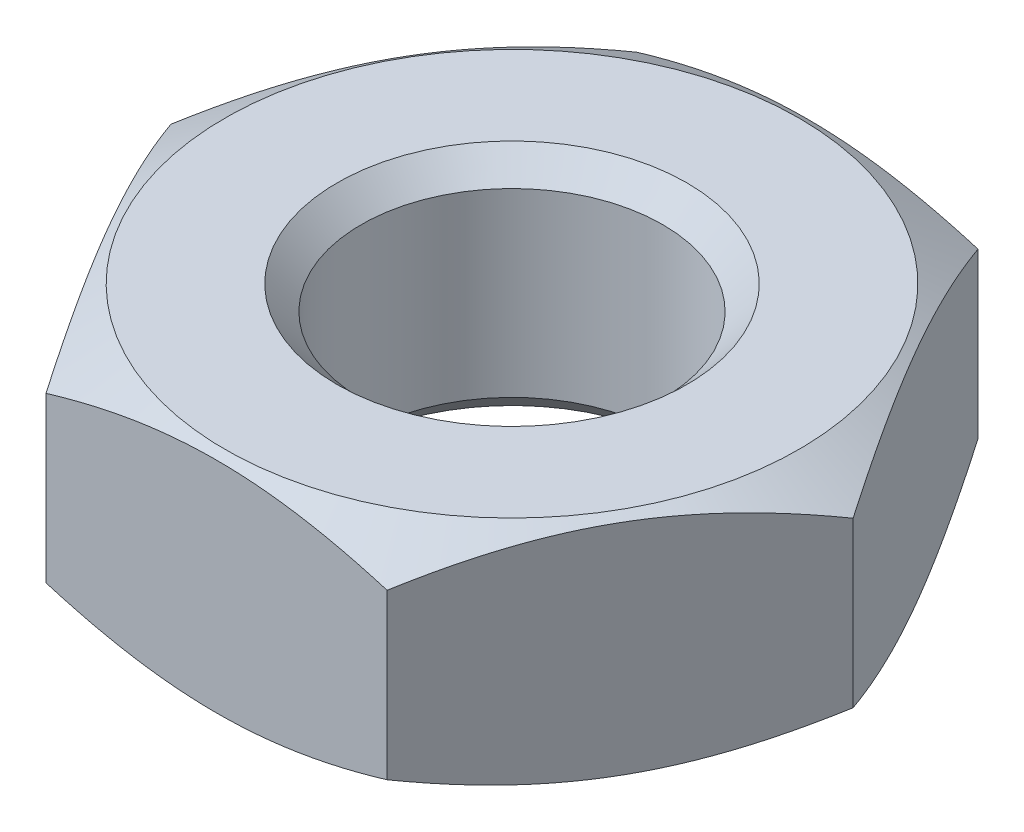
SolidWorks part; units mm, degrees
material "Plain Carbon Steel"
ref_plane "Front Plane" through (0, 0, 0) normal (0, 0, 1) x (1, 0, 0)
ref_plane "Top Plane" through (0, 0, 0) normal (0, 1, 0) x (1, 0, 0)
ref_plane "Right Plane" through (0, 0, 0) normal (1, 0, 0) x (0, 0, -1)
sketch "Sketch1" plane through (0, 0, 0) normal (0, 1, 0) x (1, 0, 0)
  line L0 (0, 0) -> (0, 2.45) construction
  line L1 (1.4145, 2.45) -> (-1.4145, 2.45)
  line L2 (-1.4145, 2.45) -> (-2.829, 0)
  line L3 (-2.829, 0) -> (-1.4145, -2.45)
  line L4 (-1.4145, -2.45) -> (1.4145, -2.45)
  line L5 (1.4145, -2.45) -> (2.829, 0)
  line L6 (2.829, 0) -> (1.4145, 2.45)
  circle A0 centre (0, 0) radius 2.45 construction
  dimension "D1" = 4.9
extrude "Boss-Extrude1" add sketch "Sketch1" along normal blind 1.9
sketch "Sketch2" plane through (0, 1.9, 0) normal (0, 1, 0) x (1, 0, 0)
  circle A0 centre (0, 0) radius 1.25
  dimension "D1" = 2.5
extrude "Cut-Extrude1" cut sketch "Sketch2" against normal through all
chamfer "Chamfer1" distance 0.2 angle 45 2 edges at (0, 0, 1.25) (0, 1.9, 1.25)
sketch "Sketch3" plane through (0, 0, 0) normal (1, 0, 0) x (0, 0, -1)
  line L0 (-2.88, 1.9) -> (-2.38, 1.9)
  line L1 (-2.45, 1.9) -> (0, 1.9) construction
  line L2 (-2.38, 1.9) -> (-2.88, 1.6)
  line L3 (-2.88, 1.6) -> (-2.88, 1.9)
  line L4 (0, 0.95) -> (-2.45, 0.95) construction
  line L5 (0, 1.9) -> (0, 0) construction
  line L6 (-2.45, 1.9) -> (-2.45, 0) construction
  line L7 (-2.88, 0.3) -> (-2.88, 0)
  line L8 (-2.38, 0) -> (-2.88, 0.3)
  line L9 (-2.88, 0) -> (-2.38, 0)
  dimension "D1" = 0.07
  dimension "D2" = 0.5
  dimension "D3" = 0.3
revolve "Cut-Revolve1" cut sketch "Sketch3" angle 360 about axis through (0, 0, 0) along (0, 1, 0)
